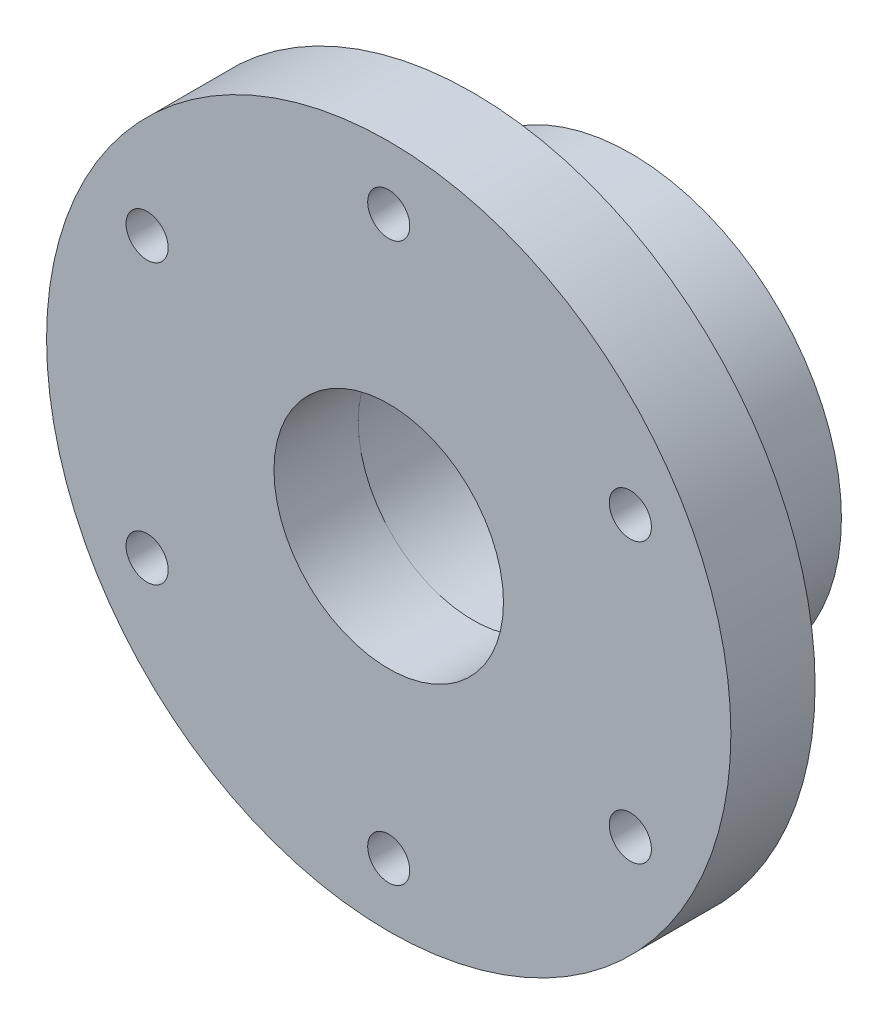
SolidWorks part; units mm, degrees
ref_plane "Спереди" through (0, 0, 0) normal (0, 0, 1) x (1, 0, 0)
ref_plane "Сверху" through (0, 0, 0) normal (0, 1, 0) x (1, 0, 0)
ref_plane "Справа" through (0, 0, 0) normal (1, 0, 0) x (0, 0, -1)
sketch "Эскиз1" plane through (0, 0, 0) normal (0, 0, 1) x (1, 0, 0)
  circle A0 centre (0, 0) radius 11
  circle A1 centre (0, 0) radius 20
extrude "Вытянуть1" add sketch "Эскиз1" along normal blind 15 from offset 50
sketch "Эскиз2" plane through (0, 0, 65) normal (0, 0, 1) x (1, 0, 0)
  circle A0 centre (0, 0) radius 10.9
  circle A1 centre (0, 0) radius 32.5
extrude "Вытянуть2" add sketch "Эскиз2" along normal blind 8
sketch "Эскиз3" plane through (0, 0, 65) normal (0, 0, -1) x (-1, 0, 0)
  circle A2 centre (0, 26.5) radius 2
  circle A3 centre (22.9497, 13.25) radius 2
  circle A4 centre (22.9497, -13.25) radius 2
  circle A5 centre (0, -26.5) radius 2
  circle A6 centre (-22.9497, -13.25) radius 2
  circle A7 centre (-22.9497, 13.25) radius 2
  dimension "D1" = 26.5
extrude "Вытянуть3" cut sketch "Эскиз3" against normal through all
